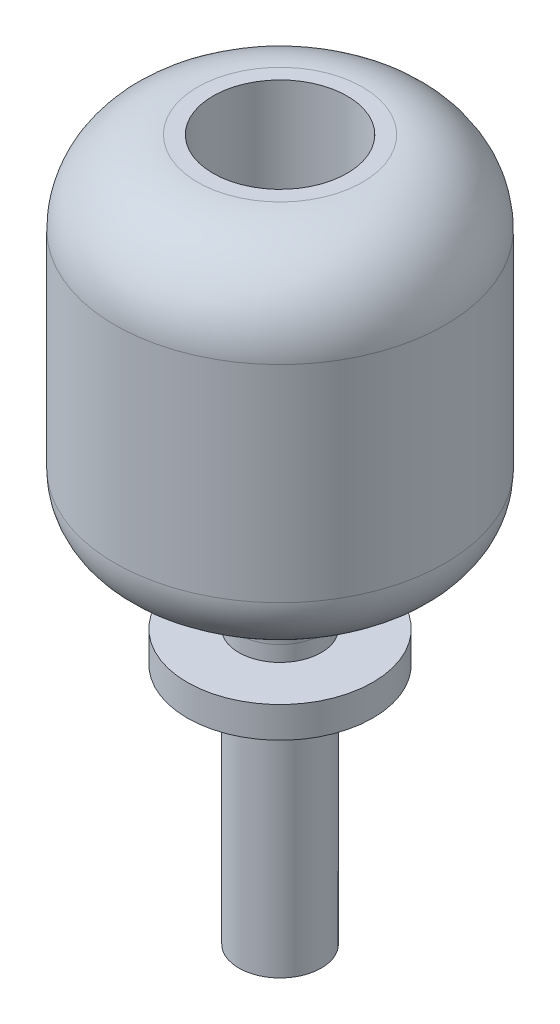
SolidWorks part; units mm, degrees
ref_plane "정면" through (0, 0, 0) normal (0, 0, 1) x (1, 0, 0)
ref_plane "윗면" through (0, 0, 0) normal (0, 1, 0) x (1, 0, 0)
ref_plane "우측면" through (0, 0, 0) normal (1, 0, 0) x (0, 0, -1)
sketch "스케치1" plane through (0, 0, 0) normal (0, 0, 1) x (1, 0, 0)
  line L0 (0, 0) -> (0, 27.1474) construction
  line L1 (0, 54.7473) -> (-8, 54.7473)
  line L2 (-16, 46.7473) -> (-16, 26.7473)
  line L3 (0, -13.2527) -> (-4, -13.2527)
  line L4 (-4, -13.2527) -> (-4, 14.7473)
  line L5 (0, 54.7473) -> (0, -13.2527)
  arc A0 (-8, 54.7473) -> (-16, 46.7473) centre (-8, 46.7473) ccw
  arc A1 (-16, 26.7473) -> (-10, 20.7473) centre (-10, 26.7473) ccw
  arc A2 (-4, 14.7473) -> (-10, 20.7473) centre (-10, 14.7473) ccw
  dimension "D2" = 8
  dimension "D4" = 6
  dimension "D5" = 6
  dimension "D1" = 8
  dimension "D3" = 20
  dimension "D6" = 4
  dimension "D7" = 0
  dimension "D8" = 28
revolve "회전2" add sketch "스케치1" angle 360 about L0
sketch "스케치2" plane through (0, 54.7473, 0) normal (0, 1, 0) x (1, 0, 0)
  circle A0 centre (0, 0) radius 6.5
extrude "컷-돌출1" cut sketch "스케치2" against normal blind 30
sketch "스케치3" plane through (0, -13.2527, 0) normal (0, -1, 0) x (1, 0, 0)
  circle A0 centre (0, 0) radius 2
extrude "컷-돌출2" cut sketch "스케치3" against normal up to next
sketch "스케치4" plane through (0, -13.2527, 0) normal (0, -1, 0) x (1, 0, 0)
  circle A0 centre (0, 0) radius 9
  circle A1 centre (0, 0) radius 2
extrude "보스-돌출4" add sketch "스케치4" against normal blind 3 from offset 23.5
